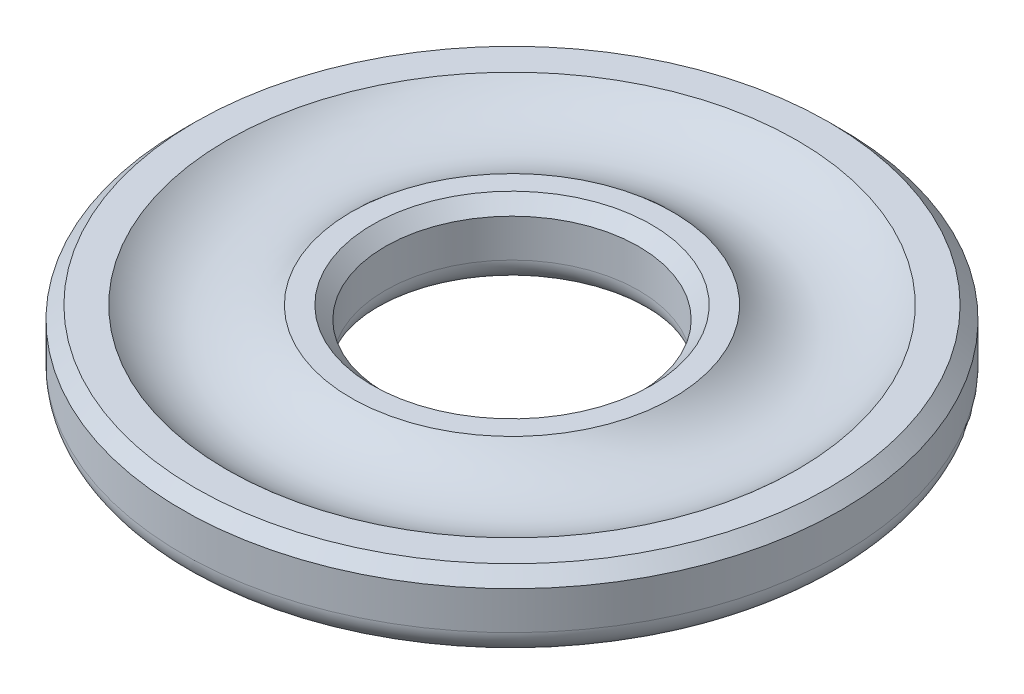
SolidWorks part; units mm, degrees
material "ABS"
ref_plane "Front Plane" through (0, 0, 0) normal (0, 0, 1) x (1, 0, 0)
ref_plane "Top Plane" through (0, 0, 0) normal (0, 1, 0) x (1, 0, 0)
ref_plane "Right Plane" through (0, 0, 0) normal (1, 0, 0) x (0, 0, -1)
sketch "Sketch1" plane through (0, 0, 0) normal (0, 0, 1) x (1, 0, 0)
  line L0 (5, -2.5) -> (6.3505, -2.5)
  line L1 (13, -2.5) -> (13, -5.5)
  line L2 (13, -5.5) -> (5, -5.5)
  line L3 (5, -5.5) -> (5, -2.5)
  line L4 (8.8, -5.5) -> (8.8, -2.5) construction
  line L5 (8.8, 5.5) -> (8.8, 2.5) construction
  line L6 (5, 2.5) -> (12.6, 2.5) construction
  line L7 (5, 2.5) -> (5, 5.5) construction
  line L8 (5, 5.5) -> (12.6, 5.5) construction
  line L9 (12.6, 2.5) -> (12.6, 5.5) construction
  line L10 (0, 0) -> (12.6, 0) construction
  line L11 (11.2495, -2.5) -> (13, -2.5)
  line L12 (6.3505, -2.5) -> (11.2495, -2.5) construction
  line L13 (0, 5.5) -> (0, -5.5) construction
  circle A0 centre (8.8, 0) radius 3 construction
  arc A1 (6.3505, -2.5) -> (11.2495, -2.5) centre (8.8, 0) ccw
  dimension "D1" = 6
  dimension "D6" = 3.5
  dimension "D2" = 5
  dimension "D3" = 13
  dimension "D4" = 3
  dimension "D5" = 8.8
  dimension "D7" = 5
revolve "Revolve1" add sketch "Sketch1" angle 360 about L13
chamfer "Chamfer1" distance 0.5 angle 45 2 edges at (-5, -2.5, 0) (-13, -2.5, 0)
fillet "Fillet2" radius 1 2 edges at (-5, -5.5, 0) (-13, -5.5, 0)
